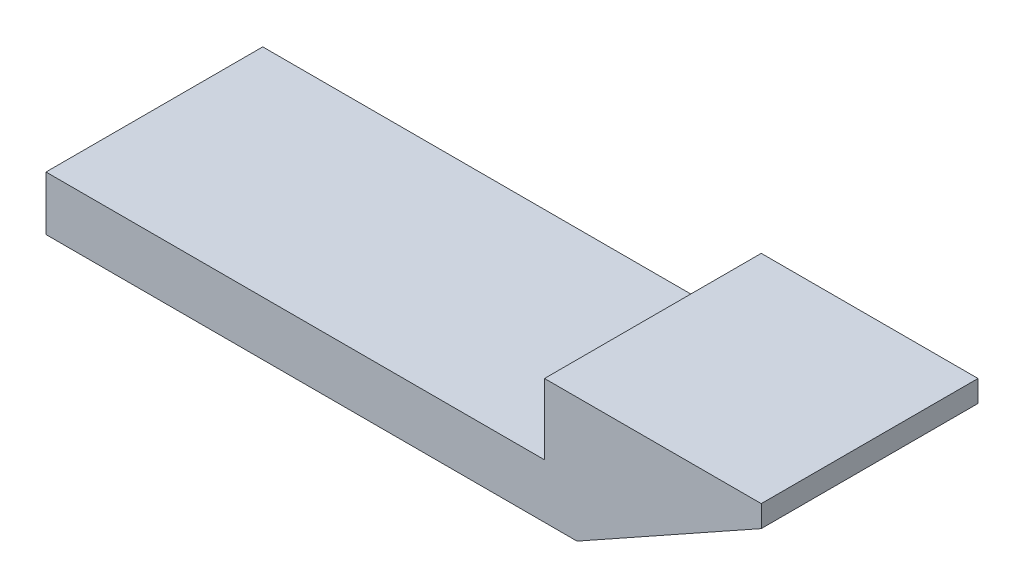
SolidWorks part; units mm, degrees
ref_plane "Alzado" through (0, 0, 0) normal (0, 0, 1) x (1, 0, 0)
ref_plane "Planta" through (0, 0, 0) normal (0, 1, 0) x (1, 0, 0)
ref_plane "Vista lateral" through (0, 0, 0) normal (1, 0, 0) x (0, 0, -1)
sketch "Croquis1" plane through (0, 0, 0) normal (0, 0, 1) x (1, 0, 0)
  line L1 (-17.0862, 0.5405) -> (28.9138, 0.5405)
  line L2 (-17.0862, 0.5405) -> (-17.0862, -4.4595)
  line L6 (28.9138, 0.5405) -> (28.9138, 7.0405)
  line L7 (28.9138, 7.0405) -> (48.9138, 7.0405)
  line L13 (-17.0862, -4.4595) -> (31.9138, -4.4595)
  line L15 (48.9138, 7.0405) -> (48.9138, 5.0405)
  line L16 (48.9138, 5.0405) -> (31.9138, -4.4595)
  dimension "D1" = 5
  dimension "D2" = 2
  dimension "D3" = 46
  dimension "D4" = 20
  dimension "D7" = 6.5
extrude "Saliente-Extruir1" add sketch "Croquis1" along normal blind 20
